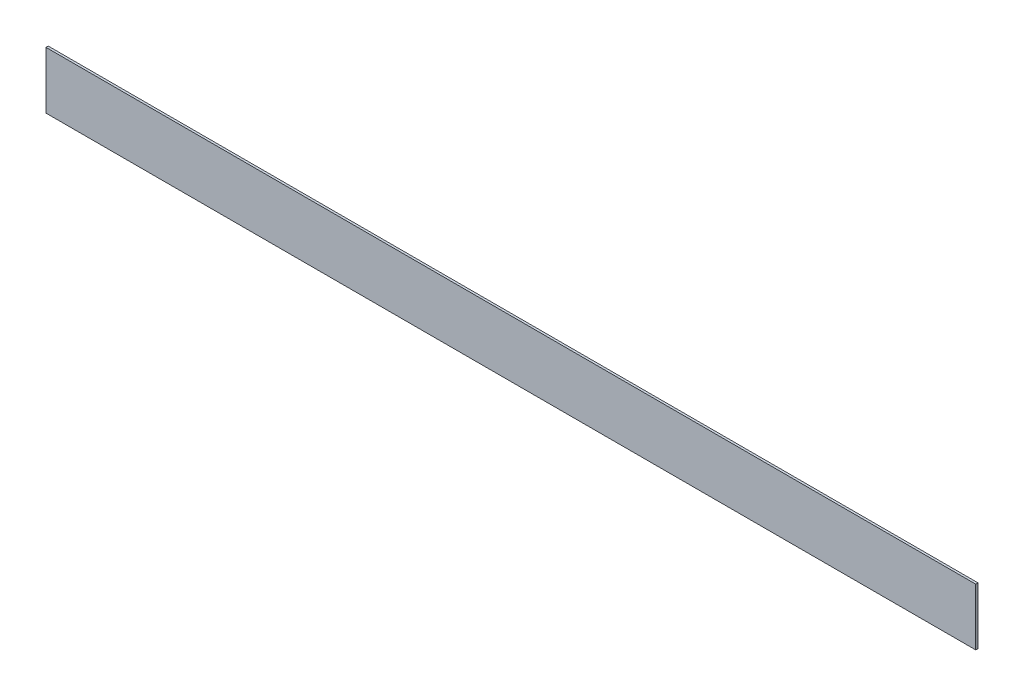
SolidWorks part; units mm, degrees
ref_plane "前视基准面" through (0, 0, 0) normal (0, 0, 1) x (1, 0, 0)
ref_plane "上视基准面" through (0, 0, 0) normal (0, 1, 0) x (1, 0, 0)
ref_plane "右视基准面" through (0, 0, 0) normal (1, 0, 0) x (0, 0, -1)
other "Configuration Table"
sketch "草图1" plane through (0, 0, 0) normal (0, 0, 1) x (1, 0, 0)
  line L1 (0, 0) -> (2056, 0)
  line L2 (0, 0) -> (0, 126)
  line L3 (0, 126) -> (2056, 126)
  line L4 (2056, 0) -> (2056, 126)
  dimension "D1" = 2056
  dimension "D2" = 126
extrude "凸台-拉伸1" add sketch "草图1" along normal blind 5
